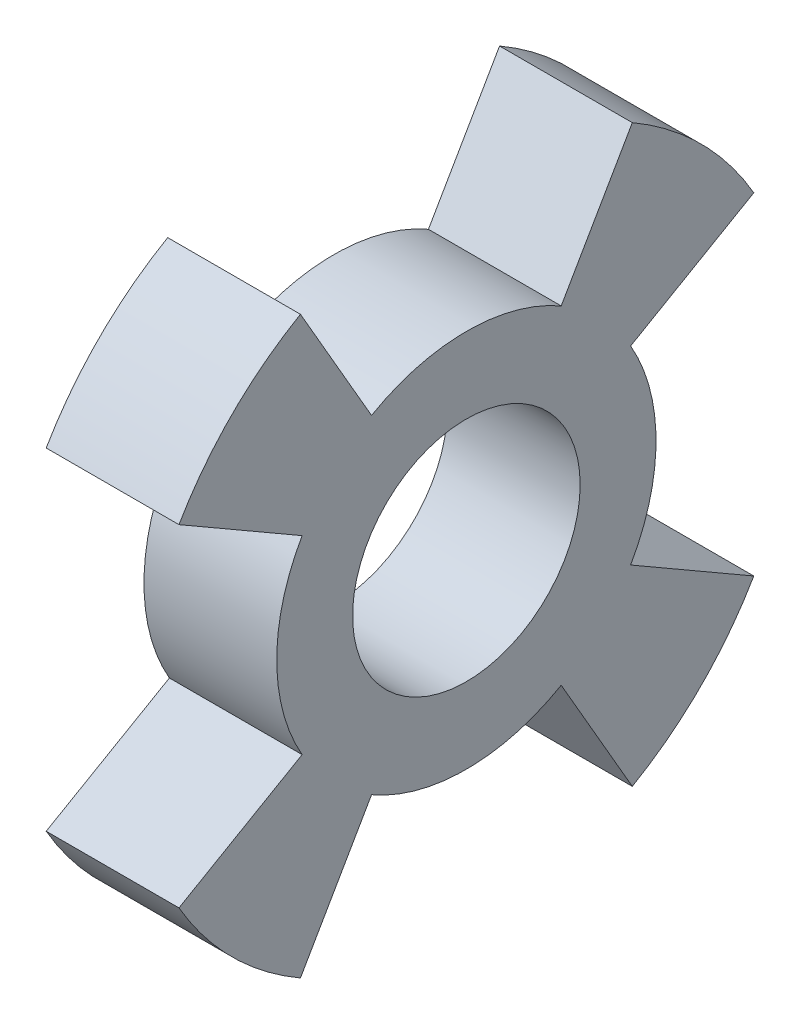
SolidWorks part; units mm, degrees
ref_plane "Front Plane" through (0, 0, 0) normal (0, 0, 1) x (1, 0, 0)
ref_plane "Top Plane" through (0, 0, 0) normal (0, 1, 0) x (1, 0, 0)
ref_plane "Right Plane" through (0, 0, 0) normal (1, 0, 0) x (0, 0, -1)
sketch "Sketch1" plane through (0, 0, 0) normal (1, 0, 0) x (0, 0, -1)
  circle A0 centre (0, 0) radius 35
  dimension "D1" = 70
extrude "Boss-Extrude1" add sketch "Sketch1" along normal blind 14
sketch "Sketch2" plane through (0, 0, 0) normal (1, 0, 0) x (0, 0, -1)
  line L0 (-17.5, 30.3109) -> (-10, 17.3205)
  line L1 (17.5, 30.3109) -> (10, 17.3205)
  line L4 (0, 7.7) -> (0, -7.7) construction
  line L5 (30.3109, 17.5) -> (17.3205, 10)
  line L6 (30.3109, -17.5) -> (17.3205, -10)
  line L7 (17.5, -30.3109) -> (10, -17.3205)
  line L8 (-17.5, -30.3109) -> (-10, -17.3205)
  line L9 (-30.3109, -17.5) -> (-17.3205, -10)
  line L10 (-30.3109, 17.5) -> (-17.3205, 10)
  circle A0 centre (0, 0) radius 35 construction
  arc A1 (10, 17.3205) -> (-10, 17.3205) centre (0, 0) ccw
  arc A2 (17.5, 30.3109) -> (-17.5, 30.3109) centre (0, 0) ccw
  arc A3 (17.3205, -10) -> (17.3205, 10) centre (0, 0) ccw
  arc A4 (30.3109, -17.5) -> (30.3109, 17.5) centre (0, 0) ccw
  arc A5 (-10, -17.3205) -> (10, -17.3205) centre (0, 0) ccw
  arc A6 (-17.5, -30.3109) -> (17.5, -30.3109) centre (0, 0) ccw
  arc A7 (-17.3205, 10) -> (-17.3205, -10) centre (0, 0) ccw
  arc A8 (-30.3109, 17.5) -> (-30.3109, -17.5) centre (0, 0) ccw
  point P7 (0, 35)
  point P26 (0, 0)
  dimension "D1" = 60
  dimension "D3" = 4
  dimension "D2" = 20
extrude "Cut-Extrude1" cut sketch "Sketch2" along normal through all
sketch "Sketch3" plane through (0, 0, 0) normal (1, 0, 0) x (0, 0, -1)
  circle A0 centre (0, 0) radius 12
extrude "Cut-Extrude2" cut sketch "Sketch3" against normal through all and the other way through all
sketch "Sketch4" plane through (0, 0, 0) normal (1, 0, 0) x (0, 0, -1)
  circle A0 centre (0, 0) radius 15
  dimension "D1" = 30
extrude "Cut-Extrude3" [suppressed] cut sketch "Sketch4" along normal through all
sketch "Sketch5" plane through (0, 0, 0) normal (1, 0, 0) x (0, 0, -1)
  circle A0 centre (0, 0) radius 17.5
  dimension "D1" = 35
extrude "Cut-Extrude4" [suppressed] cut sketch "Sketch5" along normal through all
